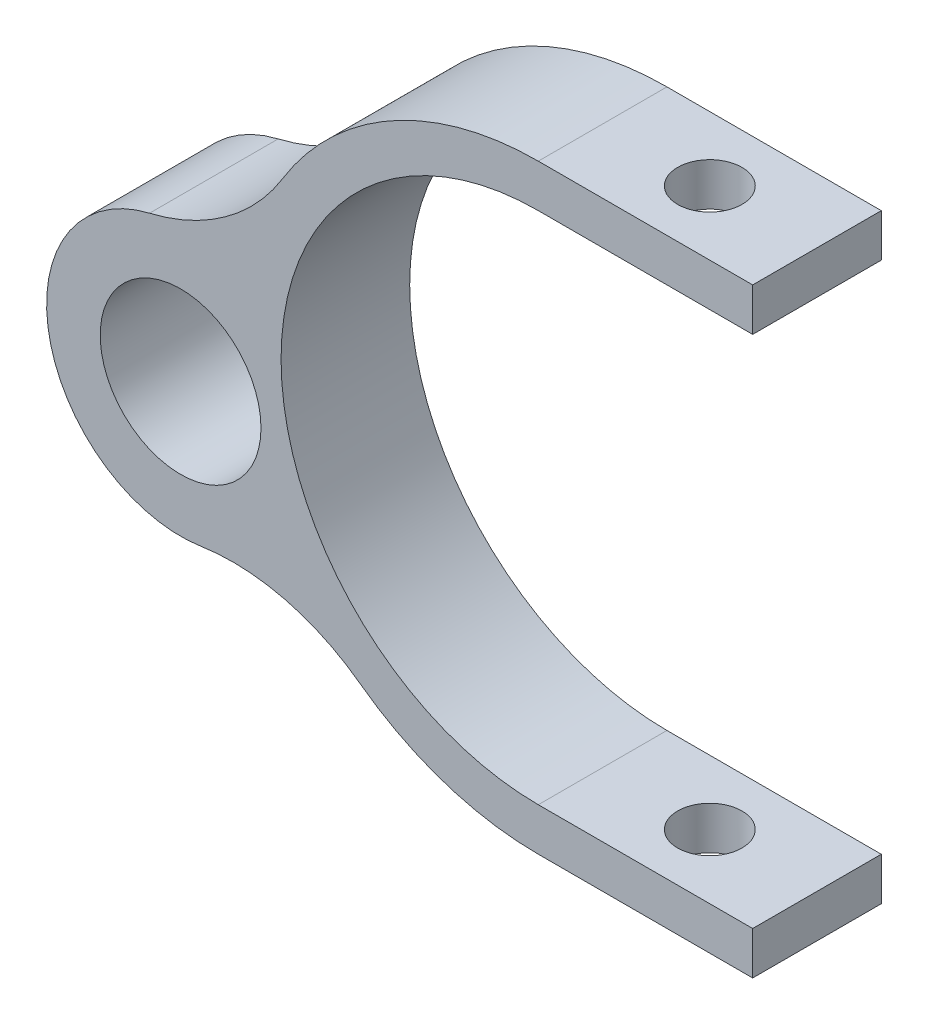
SolidWorks part; units mm, degrees
ref_plane "Front Plane" through (0, 0, 0) normal (0, 0, 1) x (1, 0, 0)
ref_plane "Top Plane" through (0, 0, 0) normal (0, 1, 0) x (1, 0, 0)
ref_plane "Right Plane" through (0, 0, 0) normal (1, 0, 0) x (0, 0, -1)
sketch "Sketch1" plane through (0, 0, 0) normal (0, 0, 1) x (1, 0, 0)
  line L0 (0, 12) -> (10, 12)
  line L1 (10, 12) -> (10, 14)
  line L2 (10, 14) -> (0, 14)
  line L3 (0, -12) -> (10, -12)
  line L4 (0, -14) -> (10, -14)
  line L5 (10, -14) -> (10, -12)
  line L6 (0, 0) -> (-16.6864, -3.25) construction
  arc A0 (0, 12) -> (0, -12) centre (0, 0) ccw
  circle A1 centre (-16.6864, -3.25) radius 3.75
  arc A2 (0, 14) -> (-13.81, 2.2987) centre (0, 0) ccw
  arc A3 (-13.81, 2.2987) -> (-11.9378, -7.3136) centre (-16.6864, -3.25) ccw
  arc A5 (-11.9378, -7.3136) -> (0, -14) centre (0, 0) ccw
  point P12 (-11.7787, -2.2941)
  dimension "D1" = 12
  dimension "D2" = 5
  dimension "D4" = 2.5
  dimension "D5" = 7.5
  dimension "D6" = 10
  dimension "D3" = 2
  dimension "D7" = 10
extrude "Boss-Extrude1" add sketch "Sketch1" along normal blind 6
sketch "Sketch2" plane through (0, 14, 0) normal (0, 1, 0) x (1, 0, 0)
  line L0 (10, 0) -> (0, -6) construction
  circle A0 centre (5, -3) radius 1.5
  dimension "D1" = 3
extrude "Cut-Extrude1" cut sketch "Sketch2" against normal blind 39
fillet "Fillet1" radius 10 2 edges at (-11.9378, -7.3136, 3) (-13.81, 2.2987, 3)
